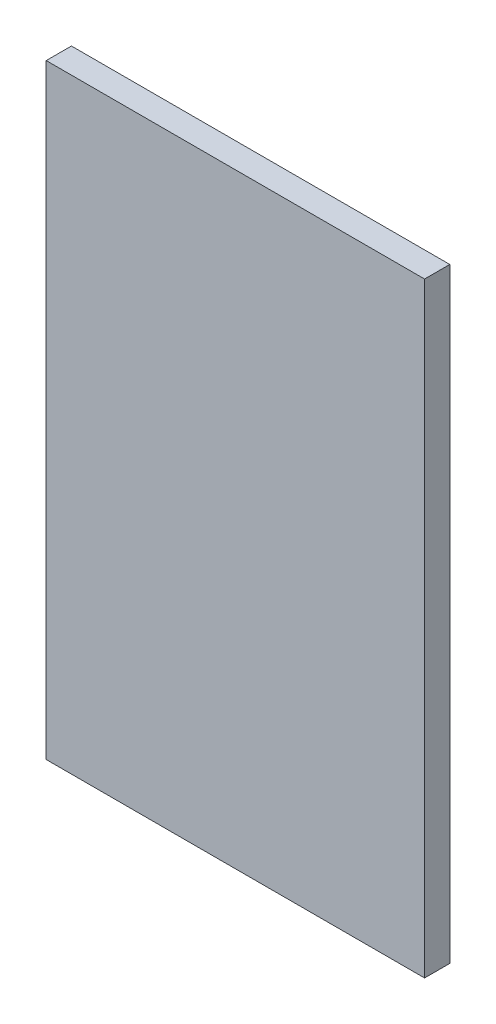
SolidWorks part; units mm, degrees
material "1.0553 (S355J0)"
ref_plane "Front Plane" through (0, 0, 0) normal (0, 0, 1) x (1, 0, 0)
ref_plane "Top Plane" through (0, 0, 0) normal (0, 1, 0) x (1, 0, 0)
ref_plane "Right Plane" through (0, 0, 0) normal (1, 0, 0) x (0, 0, -1)
sketch "Sketch1" plane through (0, 0, 0) normal (0, 0, 1) x (1, 0, 0)
  line L1 (-37.5, 0) -> (37.5, 0)
  line L2 (-37.5, 0) -> (-37.5, -120)
  line L3 (-37.5, -120) -> (37.5, -120)
  line L4 (37.5, 0) -> (37.5, -120)
  dimension "D1" = 75
  dimension "D2" = 120
extrude "Boss-Extrude1" add sketch "Sketch1" along normal blind 5
